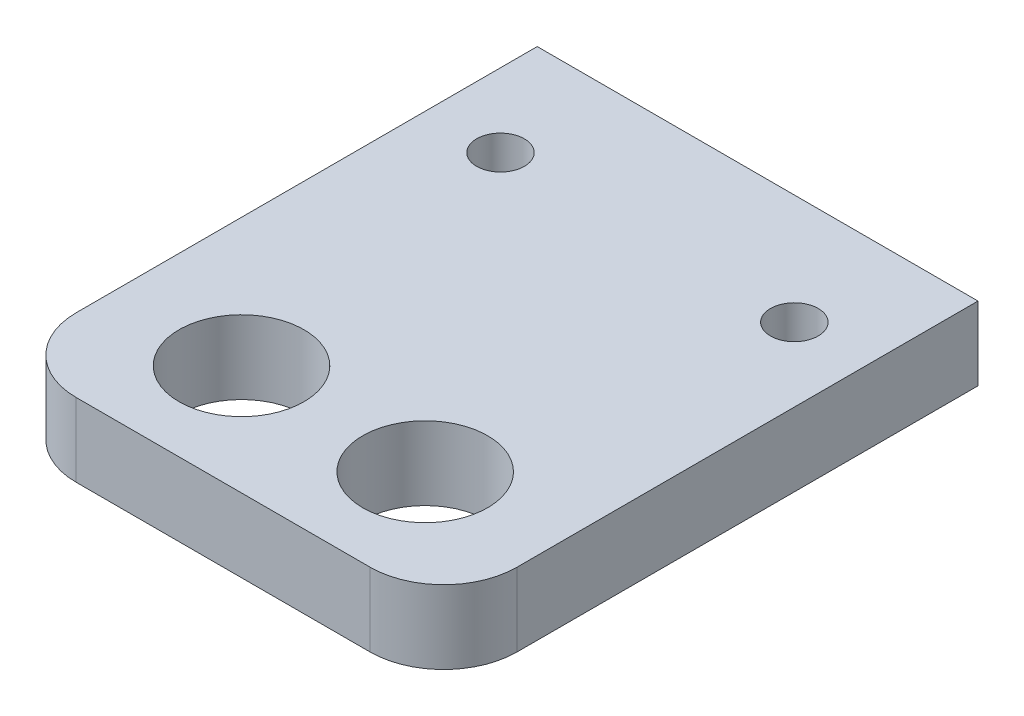
SolidWorks part; units mm, degrees
ref_plane "Front Plane" through (0, 0, 0) normal (0, 0, 1) x (1, 0, 0)
ref_plane "Top Plane" through (0, 0, 0) normal (0, 1, 0) x (1, 0, 0)
ref_plane "Right Plane" through (0, 0, 0) normal (1, 0, 0) x (0, 0, -1)
sketch "Sketch10" plane through (0, 0, 0) normal (0, 1, 0) x (1, 0, 0)
  line L16 (0, 72.75) -> (60, 72.75)
  line L17 (0, 72.75) -> (0, 0)
  line L18 (0, 0) -> (60, 0)
  line L19 (60, 72.75) -> (60, 0)
  circle A0 centre (10, 57.75) radius 3.25
  circle A1 centre (17.5, 15) radius 8.5
  circle A2 centre (50, 57.75) radius 3.25
  circle A3 centre (42.5, 15) radius 8.5
  point P6 (30, 0)
  point P9 (30, 72.75)
  dimension "D1" = 60
  dimension "D7" = 15
  dimension "D8" = 25
  dimension "D3" = 6.5
  dimension "D5" = 17
  dimension "D6" = 17
  dimension "D2" = 72.75
  dimension "D4" = 15
  dimension "D9" = 12.5
  dimension "D10" = 40
  dimension "D11" = 20
extrude "Boss-Extrude1" add sketch "Sketch10" along normal blind 10
fillet "Fillet1" radius 10 2 edges at (60, 5, 0) (0, 5, 0)
